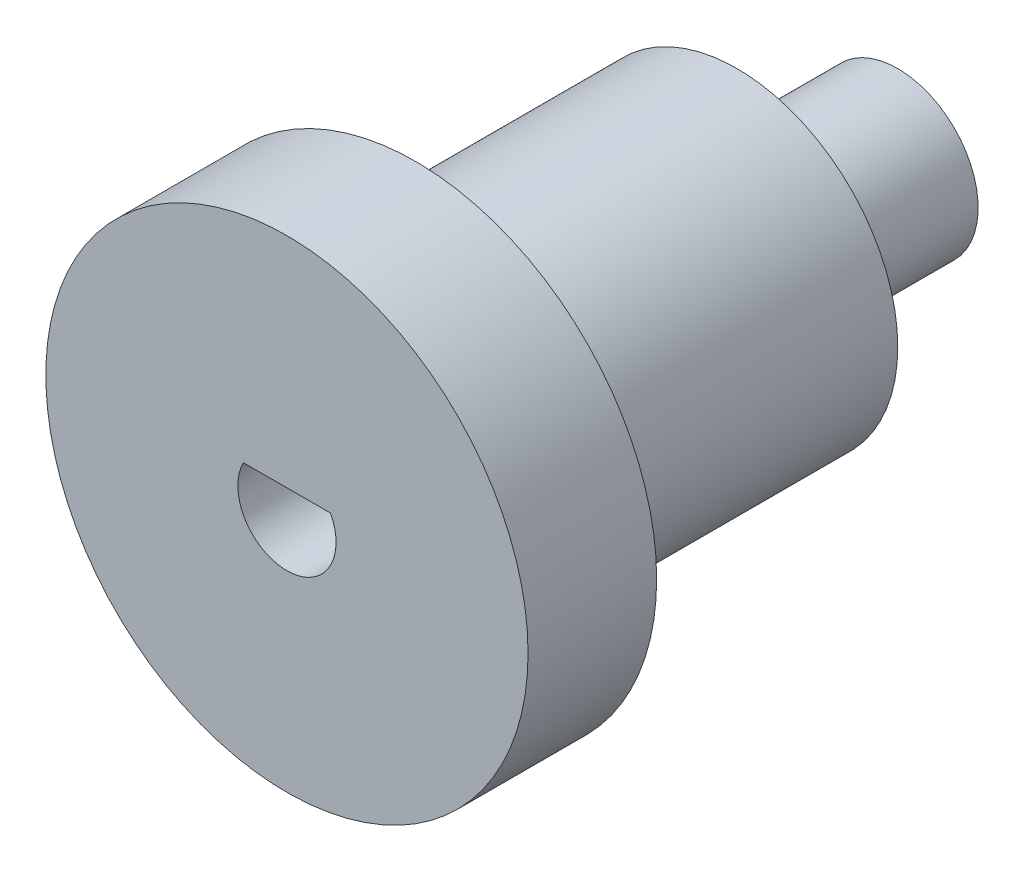
SolidWorks part; units mm, degrees
material "Delrin 2700 NC010, Low Viscosity Acetal Copolymer (SS)"
ref_plane "Front Plane" through (0, 0, 0) normal (0, 0, 1) x (1, 0, 0)
ref_plane "Top Plane" through (0, 0, 0) normal (0, 1, 0) x (1, 0, 0)
ref_plane "Right Plane" through (0, 0, 0) normal (1, 0, 0) x (0, 0, -1)
sketch "Sketch1" plane through (0, 0, 0) normal (0, 0, 1) x (1, 0, 0)
  line L0 (-1.7212, 0.895) -> (1.7212, 0.895)
  circle A0 centre (0, 0) radius 9.525
  arc A2 (-1.7212, 0.895) -> (1.7212, 0.895) centre (0, 0) ccw
  dimension "D1" = 19.05
  dimension "D2" = 1.94
  dimension "D3" = 3.4425
extrude "Boss-Extrude1" add sketch "Sketch1" along normal blind 5.08
sketch "Sketch2" plane through (0, 0, 0) normal (0, 0, -1) x (-1, 0, 0)
  circle A0 centre (0, 0) radius 6.35
  dimension "D1" = 12.7
extrude "Boss-Extrude2" add sketch "Sketch2" along normal blind 12.7
sketch "Sketch3" plane through (0, 0, -12.7) normal (0, 0, -1) x (-1, 0, 0)
  circle A0 centre (0, 0) radius 3.175
  dimension "D1" = 6.35
extrude "Boss-Extrude3" add sketch "Sketch3" along normal blind 6.35
